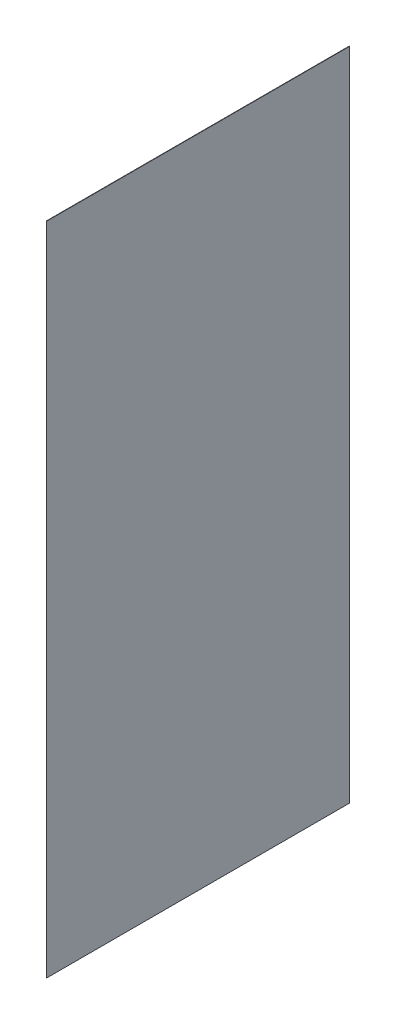
SolidWorks part; units mm, degrees
ref_plane "Front Plane" through (0, 0, 0) normal (0, 0, 1) x (1, 0, 0)
ref_plane "Top Plane" through (0, 0, 0) normal (0, 1, 0) x (1, 0, 0)
ref_plane "Right Plane" through (0, 0, 0) normal (1, 0, 0) x (0, 0, -1)
other "Configuration Table"
sketch "Sketch1" plane through (0, 0, 0) normal (0, 0, 1) x (1, 0, 0)
  line L1 (41.5, 241.5) -> (42.5, 241.5)
  line L2 (41.5, 241.5) -> (41.5, 1968.5)
  line L3 (41.5, 1968.5) -> (42.5, 1968.5)
  line L4 (42.5, 241.5) -> (42.5, 1968.5)
extrude "TOPPING_ic_yan_sol_1" add sketch "Sketch1" against normal blind 798.5 separate body
